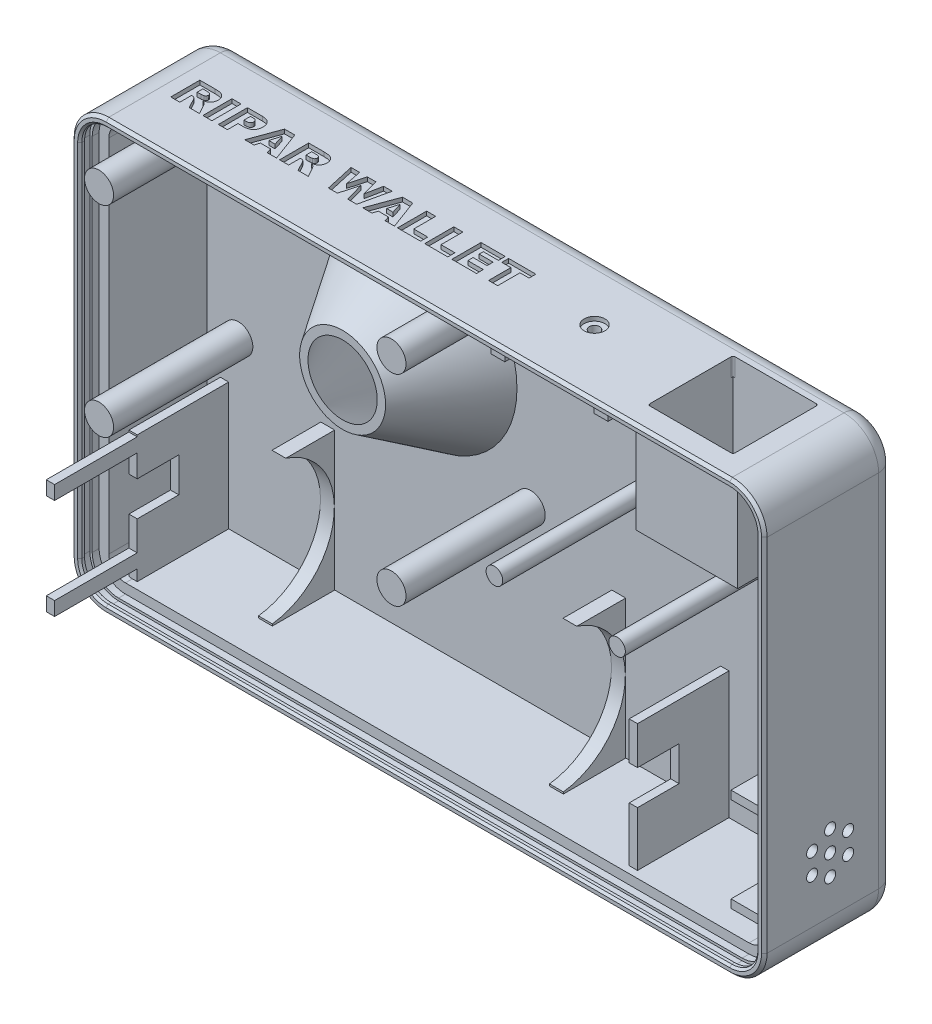
SolidWorks part; units mm, degrees
ref_plane "Front Plane" through (0, 0, 0) normal (0, 0, 1) x (1, 0, 0)
ref_plane "Top Plane" through (0, 0, 0) normal (0, 1, 0) x (1, 0, 0)
ref_plane "Right Plane" through (0, 0, 0) normal (1, 0, 0) x (0, 0, -1)
ref_plane "PZ_m13_00" through (0, 0, -13) normal (0, 0, 1) x (1, 0, 0)
sketch "Body_Sk1" plane through (0, 0, -13) normal (0, 0, 1) x (1, 0, 0)
  line L0 (-45, -31) -> (45, -31)
  line L1 (50, -26) -> (50, 26)
  line L2 (45, 31) -> (-45, 31)
  line L3 (-50, 26) -> (-50, -26)
  arc A0 (-50, -26) -> (-45, -31) centre (-45, -26) ccw
  arc A1 (45, -31) -> (50, -26) centre (45, -26) ccw
  arc A2 (50, 26) -> (45, 31) centre (45, 26) ccw
  arc A3 (-45, 31) -> (-50, 26) centre (-45, 26) ccw
extrude "Body" add sketch "Body_Sk1" against normal blind 19
fillet "Round_Back" radius 2.5 8 edges at (-48.5355, -29.5355, -32) (0, -31, -32) (48.5355, -29.5355, -32) (50, 0, -32) (48.5355, 29.5355, -32) (0, 31, -32) (-48.5355, 29.5355, -32) (-50, 0, -32)
sketch "Cavity_Sk2" plane through (0, 0, -13) normal (0, 0, 1) x (1, 0, 0)
  line L0 (-45, -28.4) -> (45, -28.4)
  line L1 (47.4, -26) -> (47.4, 26)
  line L2 (45, 28.4) -> (-45, 28.4)
  line L3 (-47.4, 26) -> (-47.4, -26)
  arc A0 (-47.4, -26) -> (-45, -28.4) centre (-45, -26) ccw
  arc A1 (45, -28.4) -> (47.4, -26) centre (45, -26) ccw
  arc A2 (47.4, 26) -> (45, 28.4) centre (45, 26) ccw
  arc A3 (-45, 28.4) -> (-47.4, 26) centre (-45, 26) ccw
extrude "Cavity" cut sketch "Cavity_Sk2" against normal blind 17
sketch "Rebate_Sk3" plane through (0, 0, -13) normal (0, 0, 1) x (1, 0, 0)
  line L0 (-45, -29.8) -> (45, -29.8)
  line L1 (48.8, -26) -> (48.8, 26)
  line L2 (45, 29.8) -> (-45, 29.8)
  line L3 (-48.8, 26) -> (-48.8, -26)
  line L4 (-45, -28.4) -> (45, -28.4)
  line L5 (47.4, -26) -> (47.4, 26)
  line L6 (45, 28.4) -> (-45, 28.4)
  line L7 (-47.4, 26) -> (-47.4, -26)
  arc A0 (-48.8, -26) -> (-45, -29.8) centre (-45, -26) ccw
  arc A1 (45, -29.8) -> (48.8, -26) centre (45, -26) ccw
  arc A2 (48.8, 26) -> (45, 29.8) centre (45, 26) ccw
  arc A3 (-45, 29.8) -> (-48.8, 26) centre (-45, 26) ccw
  arc A4 (-47.4, -26) -> (-45, -28.4) centre (-45, -26) ccw
  arc A5 (45, -28.4) -> (47.4, -26) centre (45, -26) ccw
  arc A6 (47.4, 26) -> (45, 28.4) centre (45, 26) ccw
  arc A7 (-45, 28.4) -> (-47.4, 26) centre (-45, 26) ccw
extrude "Rebate" cut sketch "Rebate_Sk3" against normal blind 2.8
ref_plane "PZ_m13_70" through (0, 0, -13.7) normal (0, 0, 1) x (1, 0, 0)
sketch "Groove_Sk4" plane through (0, 0, -13.7) normal (0, 0, 1) x (1, 0, 0)
  line L0 (-45, -30.15) -> (45, -30.15)
  line L1 (49.15, -26) -> (49.15, 26)
  line L2 (45, 30.15) -> (-45, 30.15)
  line L3 (-49.15, 26) -> (-49.15, -26)
  line L4 (-45, -29.5) -> (45, -29.5)
  line L5 (48.5, -26) -> (48.5, 26)
  line L6 (45, 29.5) -> (-45, 29.5)
  line L7 (-48.5, 26) -> (-48.5, -26)
  arc A0 (-49.15, -26) -> (-45, -30.15) centre (-45, -26) ccw
  arc A1 (45, -30.15) -> (49.15, -26) centre (45, -26) ccw
  arc A2 (49.15, 26) -> (45, 30.15) centre (45, 26) ccw
  arc A3 (-45, 30.15) -> (-49.15, 26) centre (-45, 26) ccw
  arc A4 (-48.5, -26) -> (-45, -29.5) centre (-45, -26) ccw
  arc A5 (45, -29.5) -> (48.5, -26) centre (45, -26) ccw
  arc A6 (48.5, 26) -> (45, 29.5) centre (45, 26) ccw
  arc A7 (-45, 29.5) -> (-48.5, 26) centre (-45, 26) ccw
extrude "Groove" cut sketch "Groove_Sk4" against normal blind 1.1
chamfer "Rim_LeadIn" distance 0.3 angle 45 8 edges at (0, -29.8, -13) (48.8, 0, -13) (47.687, 28.687, -13) (0, 29.8, -13) (47.687, -28.687, -13) (-47.687, 28.687, -13) (-47.687, -28.687, -13) (-48.8, 0, -13)
chamfer "Seam_Shadow" distance 0.4 angle 45 8 edges at (0, -31, -13) (50, 0, -13) (48.5355, 29.5355, -13) (0, 31, -13) (48.5355, -29.5355, -13) (-48.5355, 29.5355, -13) (-48.5355, -29.5355, -13) (-50, 0, -13)
ref_plane "PZ_m30_00" through (0, 0, -30) normal (0, 0, 1) x (1, 0, 0)
sketch "Board_Pegs_Sk5" plane through (0, 0, -30) normal (0, 0, 1) x (1, 0, 0)
  circle A0 centre (-0.71, -3.91) radius 2.1
  circle A1 centre (-0.71, 25.09) radius 2.1
  circle A2 centre (-42.915, -3.91) radius 2.1
  circle A3 centre (-42.915, 25.09) radius 2.1
extrude "Board_Pegs" add sketch "Board_Pegs_Sk5" along normal blind 20.1
sketch "Cell_Saddles_Sk6" plane through (0, 0, -30) normal (0, 0, 1) x (1, 0, 0)
  line L0 (-31, -28.4) -> (-29, -28.4)
  line L1 (-29, -28.4) -> (-29, -8.4)
  line L2 (-29, -8.4) -> (-31, -8.4)
  line L3 (-31, -8.4) -> (-31, -28.4)
  line L4 (11, -28.4) -> (13, -28.4)
  line L5 (13, -28.4) -> (13, -8.4)
  line L6 (13, -8.4) -> (11, -8.4)
  line L7 (11, -8.4) -> (11, -28.4)
extrude "Cell_Saddles" add sketch "Cell_Saddles_Sk6" along normal blind 9
sketch "Cell_Stops_Sk7" plane through (0, 0, -30) normal (0, 0, 1) x (1, 0, 0)
  line L0 (-45.5, -28.4) -> (-44.3, -28.4)
  line L1 (-44.3, -28.4) -> (-44.3, -10.05)
  line L2 (-44.3, -10.05) -> (-45.5, -10.05)
  line L3 (-45.5, -10.05) -> (-45.5, -28.4)
  line L4 (26.7, -28.4) -> (27.9, -28.4)
  line L5 (27.9, -28.4) -> (27.9, -10.05)
  line L6 (27.9, -10.05) -> (26.7, -10.05)
  line L7 (26.7, -10.05) -> (26.7, -28.4)
extrude "Cell_Stops" add sketch "Cell_Stops_Sk7" along normal blind 13.2
ref_plane "PZ_m16_80" through (0, 0, -16.8) normal (0, 0, 1) x (1, 0, 0)
sketch "TP_Keepers_Sk8" plane through (0, 0, -16.8) normal (0, 0, 1) x (1, 0, 0)
  line L0 (-45.5, -26.8) -> (-44.3, -26.8)
  line L1 (-44.3, -26.8) -> (-44.3, -24.8)
  line L2 (-44.3, -24.8) -> (-45.5, -24.8)
  line L3 (-45.5, -24.8) -> (-45.5, -26.8)
  line L4 (-45.5, -12.3) -> (-44.3, -12.3)
  line L5 (-44.3, -12.3) -> (-44.3, -10.3)
  line L6 (-44.3, -10.3) -> (-45.5, -10.3)
  line L7 (-45.5, -10.3) -> (-45.5, -12.3)
extrude "TP_Keepers" add sketch "TP_Keepers_Sk8" along normal blind 11.93
sketch "Cell_Wire_Slots_Sk9" plane through (0, 0, -16.8) normal (0, 0, 1) x (1, 0, 0)
  line L0 (-46.4, -20.55) -> (-43.4, -20.55)
  line L1 (-43.4, -20.55) -> (-43.4, -15.55)
  line L2 (-43.4, -15.55) -> (-46.4, -15.55)
  line L3 (-46.4, -15.55) -> (-46.4, -20.55)
  line L4 (25.8, -20.55) -> (28.8, -20.55)
  line L5 (28.8, -20.55) -> (28.8, -15.55)
  line L6 (28.8, -15.55) -> (25.8, -15.55)
  line L7 (25.8, -15.55) -> (25.8, -20.55)
extrude "Cell_Wire_Slots" cut sketch "Cell_Wire_Slots_Sk9" against normal blind 6
ref_plane "PX_m44_30" through (-44.3, 0, 0) normal (1, 0, 0) x (0, 0, -1)
sketch "Cell_Cavity_Sk10" plane through (-44.3, 0, 0) normal (1, 0, 0) x (0, 0, -1)
  circle A0 centre (19.8, -18.05) radius 10.15
extrude "Cell_Cavity" cut sketch "Cell_Cavity_Sk10" along normal blind 71
sketch "Lens_Hood_Sk11" plane through (0, 0, -30) normal (0, 0, 1) x (1, 0, 0)
  circle A0 centre (-16.36, 9.94) radius 13.6682
extrude "Lens_Hood" add sketch "Lens_Hood_Sk11" along normal blind 11.5 draft 33
ref_plane "PZ_m32_00" through (0, 0, -32) normal (0, 0, 1) x (1, 0, 0)
sketch "Lens_Bore_Sk12" plane through (0, 0, -32) normal (0, 0, 1) x (1, 0, 0)
  circle A0 centre (-16.36, 9.94) radius 13.767
extrude "Lens_Bore" cut sketch "Lens_Bore_Sk12" along normal blind 13.51 draft 33
sketch "Lens_Bezel_Sk13" plane through (0, 0, -32) normal (0, 0, 1) x (1, 0, 0)
  circle A0 centre (-16.36, 9.94) radius 17
  circle A1 centre (-16.36, 9.94) radius 16
extrude "Lens_Bezel" cut sketch "Lens_Bezel_Sk13" along normal blind 0.6
ref_plane "PY_p28_40" through (0, 28.4, 0) normal (0, 1, 0) x (1, 0, 0)
sketch "Switch_Cradle_Sk14" plane through (0, 28.4, 0) normal (0, 1, 0) x (1, 0, 0)
  line L0 (28.65, 30) -> (43.35, 30)
  line L1 (43.35, 30) -> (43.35, 15.8)
  line L2 (43.35, 15.8) -> (28.65, 15.8)
  line L3 (28.65, 15.8) -> (28.65, 30)
  line L4 (29.85, 28.65) -> (42.15, 28.65)
  line L5 (42.15, 28.65) -> (42.15, 16.35)
  line L6 (42.15, 16.35) -> (29.85, 16.35)
  line L7 (29.85, 16.35) -> (29.85, 28.65)
extrude "Switch_Cradle" add sketch "Switch_Cradle_Sk14" against normal blind 12.15
ref_plane "PY_p16_25" through (0, 16.25, 0) normal (0, 1, 0) x (1, 0, 0)
sketch "Switch_Floor_Sk15" plane through (0, 16.25, 0) normal (0, 1, 0) x (1, 0, 0)
  line L0 (28.65, 30) -> (43.35, 30)
  line L1 (43.35, 30) -> (43.35, 15.8)
  line L2 (43.35, 15.8) -> (28.65, 15.8)
  line L3 (28.65, 15.8) -> (28.65, 30)
  line L4 (31.25, 27.75) -> (40.75, 27.75)
  line L5 (41.25, 27.25) -> (41.25, 17.75)
  line L6 (40.75, 17.25) -> (31.25, 17.25)
  line L7 (30.75, 17.75) -> (30.75, 27.25)
  arc A0 (30.75, 27.25) -> (31.25, 27.75) centre (31.25, 27.25) cw
  arc A1 (40.75, 27.75) -> (41.25, 27.25) centre (40.75, 27.25) cw
  arc A2 (41.25, 17.75) -> (40.75, 17.25) centre (40.75, 17.75) cw
  arc A3 (31.25, 17.25) -> (30.75, 17.75) centre (31.25, 17.75) cw
extrude "Switch_Floor" add sketch "Switch_Floor_Sk15" against normal blind 1.2
ref_plane "PY_p31_00" through (0, 31, 0) normal (0, 1, 0) x (1, 0, 0)
sketch "Switch_Hole_Sk16" plane through (0, 31, 0) normal (0, 1, 0) x (1, 0, 0)
  line L0 (30.15, 28.65) -> (41.85, 28.65)
  line L1 (42.15, 28.35) -> (42.15, 16.65)
  line L2 (41.85, 16.35) -> (30.15, 16.35)
  line L3 (29.85, 16.65) -> (29.85, 28.35)
  arc A0 (29.85, 28.35) -> (30.15, 28.65) centre (30.15, 28.35) cw
  arc A1 (41.85, 28.65) -> (42.15, 28.35) centre (41.85, 28.35) cw
  arc A2 (42.15, 16.65) -> (41.85, 16.35) centre (41.85, 16.65) cw
  arc A3 (30.15, 16.35) -> (29.85, 16.65) centre (30.15, 16.65) cw
extrude "Switch_Hole" cut sketch "Switch_Hole_Sk16" against normal blind 2.8
sketch "Mic_Rails_Sk17" plane through (0, 28.4, 0) normal (0, 1, 0) x (1, 0, 0)
  line L0 (7.55, 30) -> (8.75, 30)
  line L1 (8.75, 30) -> (8.75, 16)
  line L2 (8.75, 16) -> (7.55, 16)
  line L3 (7.55, 16) -> (7.55, 30)
  line L4 (23.25, 30) -> (24.45, 30)
  line L5 (24.45, 30) -> (24.45, 16)
  line L6 (24.45, 16) -> (23.25, 16)
  line L7 (23.25, 16) -> (23.25, 30)
extrude "Mic_Rails" add sketch "Mic_Rails_Sk17" against normal blind 2
ref_plane "PY_p27_25" through (0, 27.25, 0) normal (0, 1, 0) x (1, 0, 0)
sketch "Mic_Lips_Sk18" plane through (0, 27.25, 0) normal (0, 1, 0) x (1, 0, 0)
  line L0 (8.35, 30) -> (9.55, 30)
  line L1 (9.55, 30) -> (9.55, 16)
  line L2 (9.55, 16) -> (8.35, 16)
  line L3 (8.35, 16) -> (8.35, 30)
  line L4 (22.45, 30) -> (23.65, 30)
  line L5 (23.65, 30) -> (23.65, 16)
  line L6 (23.65, 16) -> (22.45, 16)
  line L7 (22.45, 16) -> (22.45, 30)
extrude "Mic_Lips" add sketch "Mic_Lips_Sk18" against normal blind 0.85
sketch "Mic_Hole_Sk19" plane through (0, 31, 0) normal (0, 1, 0) x (1, 0, 0)
  circle A0 centre (16, 22.5) radius 0.75
extrude "Mic_Hole" cut sketch "Mic_Hole_Sk19" against normal blind 2.8
sketch "Mic_Csk_Sk20" plane through (0, 31, 0) normal (0, 1, 0) x (1, 0, 0)
  circle A0 centre (16, 22.5) radius 1.5
extrude "Mic_Csk" cut sketch "Mic_Csk_Sk20" against normal blind 0.6
ref_plane "PX_p47_40" through (47.4, 0, 0) normal (1, 0, 0) x (0, 0, -1)
sketch "Buzzer_Cradle_Block_Sk21" plane through (47.4, 0, 0) normal (1, 0, 0) x (0, 0, -1)
  line L0 (30, -25.4) -> (30, -10.6)
  line L1 (30, -10.6) -> (15.8, -10.6)
  line L2 (15.8, -10.6) -> (15.8, -25.4)
  line L3 (15.8, -25.4) -> (30, -25.4)
extrude "Buzzer_Cradle_Block" add sketch "Buzzer_Cradle_Block_Sk21" against normal blind 5
ref_plane "PX_p47_41" through (47.41, 0, 0) normal (1, 0, 0) x (0, 0, -1)
sketch "Buzzer_Pocket_Sk22" plane through (47.41, 0, 0) normal (1, 0, 0) x (0, 0, -1)
  line L0 (13.5, -24.2) -> (22.5, -24.2)
  line L1 (22.5, -11.8) -> (13.5, -11.8)
  line L2 (13.5, -11.8) -> (13.5, -24.2)
  arc A0 (22.5, -24.2) -> (22.5, -11.8) centre (22.5, -18) ccw
extrude "Buzzer_Pocket" cut sketch "Buzzer_Pocket_Sk22" against normal blind 5.01
ref_plane "PX_p50_00" through (50, 0, 0) normal (1, 0, 0) x (0, 0, -1)
sketch "Buzzer_Holes_Sk23" plane through (50, 0, 0) normal (1, 0, 0) x (0, 0, -1)
  circle A0 centre (22.5, -18) radius 0.8
  circle A1 centre (22.5, -15) radius 0.8
  circle A2 centre (19.9019, -16.5) radius 0.8
  circle A3 centre (19.9019, -19.5) radius 0.8
  circle A4 centre (22.5, -21) radius 0.8
  circle A5 centre (25.0981, -19.5) radius 0.8
  circle A6 centre (25.0981, -16.5) radius 0.8
extrude "Buzzer_Holes" cut sketch "Buzzer_Holes_Sk23" against normal blind 2.8
sketch "Buzzer_Chamber_Sk24" plane through (47.4, 0, 0) normal (1, 0, 0) x (0, 0, -1)
  circle A0 centre (22.5, -18) radius 5
extrude "Buzzer_Chamber" cut sketch "Buzzer_Chamber_Sk24" along normal blind 1.3
sketch "MAX_Posts_Sk25" plane through (0, 0, -30) normal (0, 0, 1) x (1, 0, 0)
  circle A0 centre (20.15, 11) radius 1.2
  circle A1 centre (37.85, 11) radius 1.2
extrude "MAX_Posts" add sketch "MAX_Posts_Sk25" along normal blind 26.1
sketch "Txt_Top_Sk26" plane through (0, 31, 0) normal (0, 1, 0) x (1, 0, 0)
  text T0 "RIPAR WALLET" font "Arial Black" height 4.2
extrude "Txt_Top" cut sketch "Txt_Top_Sk26" against normal blind 0.6
ref_plane "PY_m31_00" through (0, -31, 0) normal (0, 1, 0) x (1, 0, 0)
sketch "Txt_Bottom_Sk27" plane through (0, -31, 0) normal (0, 1, 0) x (1, 0, 0)
  text T0 "RIPAR WALLET" font "Arial Black" height 5.5
extrude "Txt_Bottom" cut sketch "Txt_Bottom_Sk27" along normal blind 0.6
sketch "Txt_Back_Sk28" plane through (0, 0, -32) normal (0, 0, 1) x (1, 0, 0)
  text T0 "RIPAR" font "Arial Black" height 6
extrude "Txt_Back" cut sketch "Txt_Back_Sk28" along normal blind 0.8
